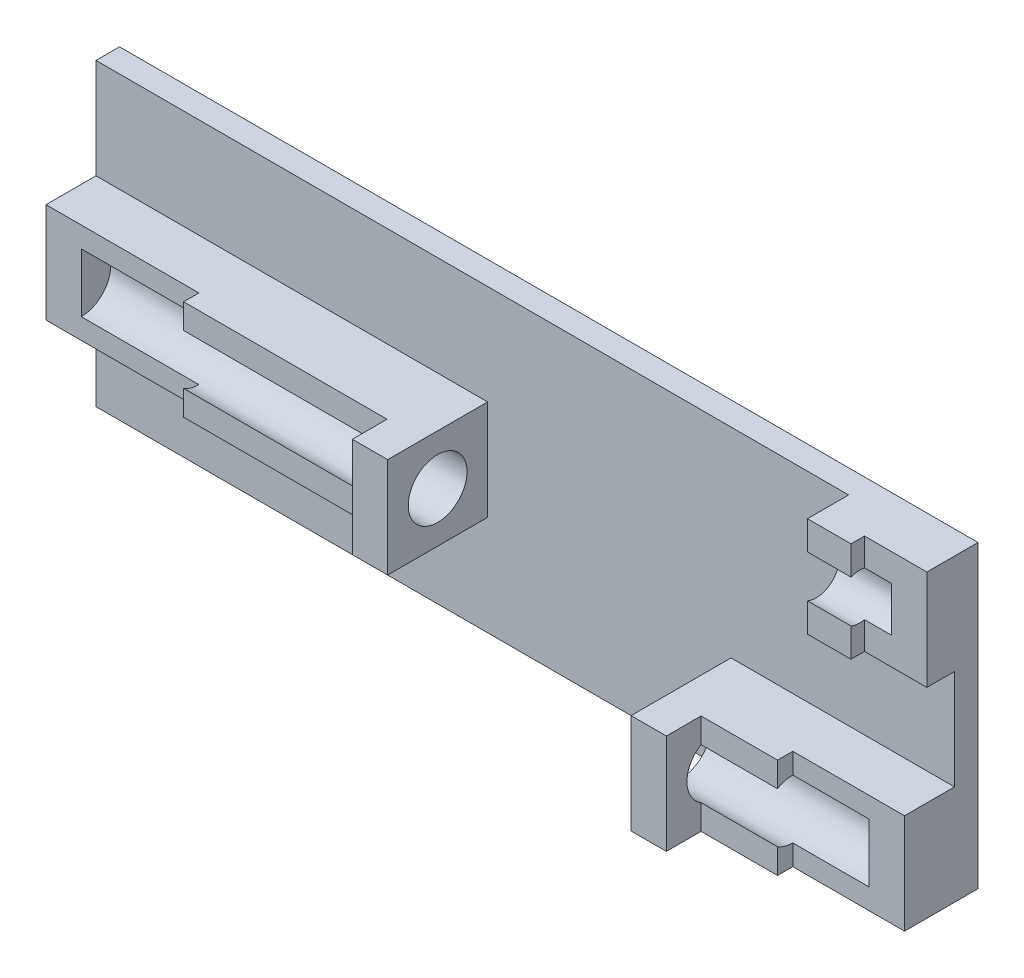
SolidWorks part; units mm, degrees
ref_plane "Alzado" through (0, 0, 0) normal (0, 0, 1) x (1, 0, 0)
ref_plane "Planta" through (0, 0, 0) normal (0, 1, 0) x (1, 0, 0)
ref_plane "Vista lateral" through (0, 0, 0) normal (1, 0, 0) x (0, 0, -1)
sketch "Croquis1" plane through (0, 0, 0) normal (0, 0, 1) x (1, 0, 0)
  line L1 (-86.5464, 20.9467) -> (-13.5464, 20.9467)
  line L2 (-86.5464, 20.9467) -> (-86.5464, -4.5533)
  line L3 (-86.5464, -4.5533) -> (-13.5464, -4.5533)
  line L4 (-13.5464, 20.9467) -> (-13.5464, -4.5533)
  dimension "D1" = 73
  dimension "D2" = 25.5
extrude "Saliente-Extruir1" add sketch "Croquis1" along normal blind 2
sketch "Croquis2" plane through (0, 0, 2) normal (0, 0, 1) x (1, 0, 0)
  line L0 (-86.5464, 20.9467) -> (-86.5464, -4.5533) construction
  line L1 (-13.5464, 20.9467) -> (-16.5464, 20.9467)
  line L2 (-13.5464, 20.9467) -> (-13.5464, 12.4467)
  line L3 (-13.5464, 12.4467) -> (-16.5464, 12.4467)
  line L4 (-16.5464, 20.9467) -> (-16.5464, 12.4467)
  line L5 (-13.5464, -4.5533) -> (-16.5464, -4.5533)
  line L6 (-13.5464, -4.5533) -> (-13.5464, 3.9467)
  line L7 (-13.5464, 3.9467) -> (-16.5464, 3.9467)
  line L8 (-16.5464, -4.5533) -> (-16.5464, 3.9467)
  line L9 (-86.5464, 12.4467) -> (-83.5464, 12.4467)
  line L10 (-86.5464, 12.4467) -> (-86.5464, 3.9467)
  line L11 (-86.5464, 3.9467) -> (-83.5464, 3.9467)
  line L12 (-83.5464, 12.4467) -> (-83.5464, 3.9467)
  line L13 (-13.5464, 20.9467) -> (-86.5464, 20.9467) construction
  line L14 (-19.5464, 12.4467) -> (-22.5464, 12.4467)
  line L15 (-19.5464, 12.4467) -> (-19.5464, 20.9467)
  line L16 (-19.5464, 20.9467) -> (-22.5464, 20.9467)
  line L17 (-22.5464, 12.4467) -> (-22.5464, 20.9467)
  line L18 (-86.5464, -4.5533) -> (-13.5464, -4.5533) construction
  line L19 (-32.5464, 3.9467) -> (-29.5464, 3.9467)
  line L20 (-32.5464, 3.9467) -> (-32.5464, -4.5533)
  line L21 (-32.5464, -4.5533) -> (-29.5464, -4.5533)
  line L22 (-29.5464, 3.9467) -> (-29.5464, -4.5533)
  line L24 (-56.2464, 12.4467) -> (-53.2464, 12.4467)
  line L25 (-56.2464, 12.4467) -> (-56.2464, 3.9467)
  line L26 (-56.2464, 3.9467) -> (-53.2464, 3.9467)
  line L27 (-53.2464, 12.4467) -> (-53.2464, 3.9467)
  dimension "D1" = 8.5
  dimension "D2" = 3
  dimension "D3" = 8.5
  dimension "D4" = 3
  dimension "D5" = 3
  dimension "D6" = 3
  dimension "D7" = 3
  dimension "D8" = 3
  dimension "D9" = 13
  dimension "D10" = 3
  dimension "D11" = 27.3
extrude "Saliente-Extruir2" add sketch "Croquis2" along normal blind 8.5
sketch "Croquis4" plane through (0, 0, 2) normal (0, 0, 1) x (1, 0, 0)
  line L1 (-29.5464, 3.9467) -> (-16.5464, 3.9467)
  line L2 (-29.5464, 3.9467) -> (-29.5464, -4.5533)
  line L3 (-29.5464, -4.5533) -> (-16.5464, -4.5533)
  line L4 (-16.5464, 3.9467) -> (-16.5464, -4.5533)
  line L5 (-83.5464, 3.9467) -> (-56.2464, 3.9467)
  line L6 (-83.5464, 3.9467) -> (-83.5464, 12.4467)
  line L7 (-83.5464, 12.4467) -> (-56.2464, 12.4467)
  line L8 (-56.2464, 3.9467) -> (-56.2464, 12.4467)
extrude "Saliente-Extruir3" add sketch "Croquis4" along normal blind 6.05
sketch "Croquis5" plane through (-32.5464, 0, 0) normal (-1, 0, 0) x (0, 0, 1)
  line L0 (10.5, 3.9467) -> (2, -4.5533) construction
  line L1 (2, -4.5533) -> (10.5, -4.5533) construction
  line L2 (10.5, -4.5533) -> (2, 3.9467) construction
  circle A0 centre (6.25, -0.3033) radius 2.5
extrude "Cortar-Extruir1" cut sketch "Croquis5" against normal up to vertex
sketch "Croquis6" plane through (-53.2464, 0, 0) normal (1, 0, 0) x (0, 0, -1)
  line L0 (-2, 12.4467) -> (-10.5, 3.9467) construction
  line L1 (-10.5, 3.9467) -> (-10.5, 12.4467) construction
  line L2 (-10.5, 12.4467) -> (-2, 3.9467) construction
  circle A0 centre (-6.25, 8.1967) radius 2.5
extrude "Cortar-Extruir2" cut sketch "Croquis6" against normal up to vertex
sketch "Croquis7" plane through (0, 0, 8.05) normal (0, 0, 1) x (1, 0, 0)
  line L0 (-83.5464, 3.9467) -> (-56.2464, 3.9467) construction
  line L1 (-83.5464, 12.4467) -> (-73.5464, 12.4467)
  line L2 (-83.5464, 12.4467) -> (-83.5464, 3.9467)
  line L3 (-83.5464, 3.9467) -> (-73.5464, 3.9467)
  line L4 (-73.5464, 12.4467) -> (-73.5464, 3.9467)
  line L5 (-29.5464, -4.5533) -> (-16.5464, -4.5533) construction
  line L6 (-16.5464, 3.9467) -> (-23.0464, 3.9467)
  line L7 (-16.5464, 3.9467) -> (-16.5464, -4.5533)
  line L8 (-16.5464, -4.5533) -> (-23.0464, -4.5533)
  line L9 (-23.0464, 3.9467) -> (-23.0464, -4.5533)
  dimension "D1" = 10
extrude "Cortar-Extruir3" cut sketch "Croquis7" against normal blind 1.8
sketch "Croquis8" plane through (0, 0, 2) normal (0, 0, 1) x (1, 0, 0)
  line L1 (-19.5464, 12.4467) -> (-16.5464, 12.4467)
  line L2 (-19.5464, 12.4467) -> (-19.5464, 20.9467)
  line L3 (-19.5464, 20.9467) -> (-16.5464, 20.9467)
  line L4 (-16.5464, 12.4467) -> (-16.5464, 20.9467)
extrude "Saliente-Extruir4" add sketch "Croquis8" along normal blind 4.85
sketch "Croquis9" plane through (-22.5464, 0, 0) normal (-1, 0, 0) x (0, 0, 1)
  line L0 (2, 20.9467) -> (2, 12.4467) construction
  line L1 (2, 20.9467) -> (10.5, 20.9467) construction
  circle A0 centre (4.75, 16.6967) radius 1.95
  dimension "D1" = 2.75
extrude "Cortar-Extruir4" cut sketch "Croquis9" against normal up to vertex (6 mm away)
sketch "Croquis10" plane through (0, 0, 10.5) normal (0, 0, 1) x (1, 0, 0)
  line L1 (-13.5464, 20.9467) -> (-16.5464, 20.9467)
  line L2 (-13.5464, 20.9467) -> (-13.5464, 12.4467)
  line L3 (-13.5464, 12.4467) -> (-16.5464, 12.4467)
  line L4 (-16.5464, 20.9467) -> (-16.5464, 12.4467)
extrude "Cortar-Extruir5" cut sketch "Croquis10" against normal up to vertex
sketch "Croquis11" plane through (0, 0, 10.5) normal (0, 0, 1) x (1, 0, 0)
  line L1 (-16.5464, -4.5533) -> (-13.5464, -4.5533)
  line L2 (-16.5464, -4.5533) -> (-16.5464, 3.9467)
  line L3 (-16.5464, 3.9467) -> (-13.5464, 3.9467)
  line L4 (-13.5464, -4.5533) -> (-13.5464, 3.9467)
  line L5 (-83.5464, 3.9467) -> (-86.5464, 3.9467)
  line L6 (-83.5464, 3.9467) -> (-83.5464, 12.4467)
  line L7 (-83.5464, 12.4467) -> (-86.5464, 12.4467)
  line L8 (-86.5464, 3.9467) -> (-86.5464, 12.4467)
extrude "Cortar-Extruir6" cut sketch "Croquis11" against normal up to vertex
sketch "Croquis12" plane through (0, 0, 8.05) normal (0, 0, 1) x (1, 0, 0)
  line L1 (-73.5464, 12.4467) -> (-56.2464, 12.4467)
  line L2 (-73.5464, 12.4467) -> (-73.5464, 3.9467)
  line L3 (-73.5464, 3.9467) -> (-56.2464, 3.9467)
  line L4 (-56.2464, 12.4467) -> (-56.2464, 3.9467)
  line L5 (-29.5464, 3.9467) -> (-23.0464, 3.9467)
  line L6 (-29.5464, 3.9467) -> (-29.5464, -4.5533)
  line L7 (-29.5464, -4.5533) -> (-23.0464, -4.5533)
  line L8 (-23.0464, 3.9467) -> (-23.0464, -4.5533)
extrude "Cortar-Extruir7" cut sketch "Croquis12" against normal blind 0.5
sketch "Croquis13" plane through (0, 0, 6.85) normal (0, 0, 1) x (1, 0, 0)
  line L5 (-13.5464, 12.4467) -> (-18.8464, 12.4467)
  line L6 (-13.5464, 12.4467) -> (-13.5464, 20.9467)
  line L7 (-13.5464, 20.9467) -> (-18.8464, 20.9467)
  line L8 (-18.8464, 12.4467) -> (-18.8464, 20.9467)
extrude "Cortar-Extruir8" cut sketch "Croquis13" against normal blind 2.5
sketch "Croquis15" plane through (0, 0, 10.5) normal (0, 0, 1) x (1, 0, 0)
  line L5 (-22.5464, 20.9467) -> (-18.0464, 20.9467)
  line L6 (-22.5464, 20.9467) -> (-22.5464, 12.4467)
  line L7 (-22.5464, 12.4467) -> (-18.0464, 12.4467)
  line L8 (-18.0464, 20.9467) -> (-18.0464, 12.4467)
  dimension "D1" = 4.5
extrude "Cortar-Extruir9" cut sketch "Croquis15" against normal blind 5
